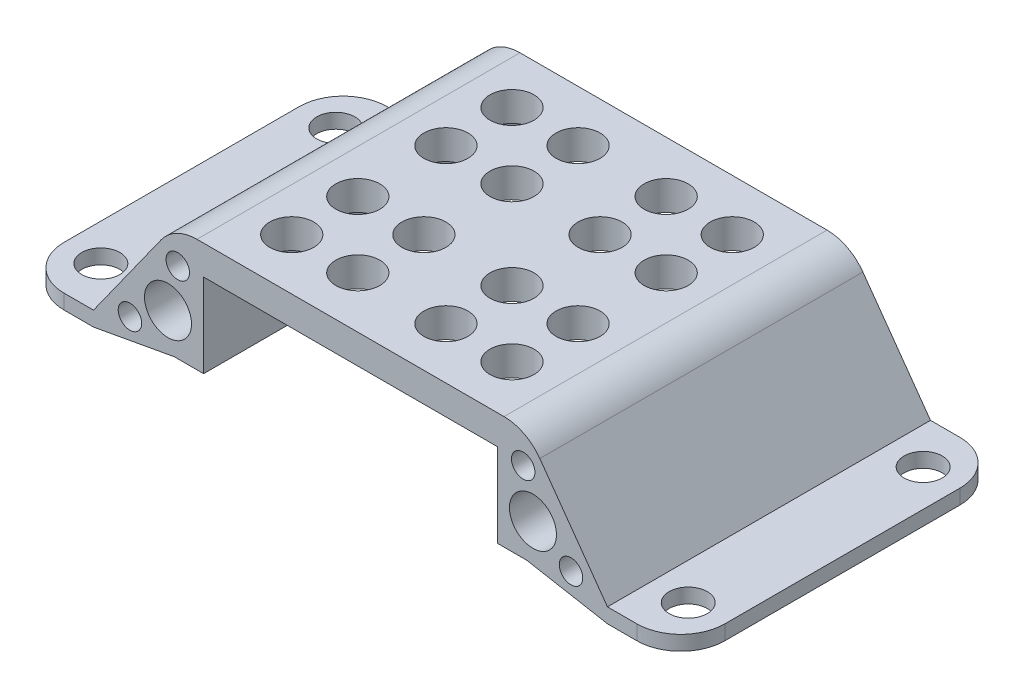
SolidWorks part; units mm, degrees
ref_plane "前视基准面" through (0, 0, 0) normal (0, 0, 1) x (1, 0, 0)
ref_plane "上视基准面" through (0, 0, 0) normal (0, 1, 0) x (1, 0, 0)
ref_plane "右视基准面" through (0, 0, 0) normal (1, 0, 0) x (0, 0, -1)
sketch "草图1" plane through (0, 0, 0) normal (0, 0, 1) x (1, 0, 0)
  line L0 (0, 0) -> (0, 12.8298) construction
  line L1 (12, 5.1298) -> (17.5, 4.1298)
  line L2 (0, 12.8298) -> (12, 12.8298)
  line L3 (0, 12.8298) -> (0, 10.8298)
  line L4 (0, 10.8298) -> (12, 10.8298)
  line L5 (12, 12.8298) -> (12, 10.8298)
  line L10 (17.5, 4.1298) -> (22.5, 4.1298)
  line L11 (17.5, 4.1298) -> (17.5, 5.1298)
  line L12 (17.5, 5.1298) -> (22.5, 5.1298)
  line L13 (22.5, 4.1298) -> (22.5, 5.1298)
  line L14 (10, 10.8298) -> (12, 10.8298)
  line L15 (10, 10.8298) -> (10, 5.1298)
  line L16 (10, 5.1298) -> (12, 5.1298)
  line L17 (12, 10.8298) -> (12, 5.1298)
  line L18 (12, 12.8298) -> (17.5, 5.1298)
  dimension "D1" = 2
  dimension "D2" = 17.5
  dimension "D3" = 1
  dimension "D4" = 6.7
  dimension "D5" = 5
  dimension "D7" = 2
  dimension "D8" = 5.7
  dimension "D9" = 10
extrude "凸台-拉伸1" add sketch "草图1" along normal blind 22
mirror "镜向1" about plane through (0, 0, 22) normal (1, 0, 0) of "凸台-拉伸1"
sketch "草图5" plane through (0, 0, 0) normal (0, 1, 0) x (1, 0, 0)
  line L0 (0, 0) -> (0, -22) construction
  line L1 (-12, -22) -> (12, -22) construction
  line L2 (-22.5, -11) -> (22.5, -11) construction
  line L3 (-22.5, -22) -> (-22.5, 0) construction
  line L4 (22.5, -22) -> (22.5, 0) construction
  circle A0 centre (-20, -3) radius 1.3
  circle A1 centre (-20, -19) radius 1.3
  circle A2 centre (20, -19) radius 1.3
  circle A3 centre (20, -3) radius 1.3
  dimension "D1" = 20
  dimension "D2" = 8
extrude "切除-拉伸2" cut sketch "草图5" along normal blind 19 contours A0 | A1 | A3 | A2
fillet "圆角1" radius 3 4 edges at (-22.5, 4.6298, 0) (-22.5, 4.6298, 22) (22.5, 4.6298, 0) (22.5, 4.6298, 22)
sketch "草图6" plane through (0, 0, 0) normal (0, 1, 0) x (1, 0, 0)
  line L0 (-22.5, -11) -> (22.5, -11) construction
  line L1 (-22.5, -19) -> (-22.5, -3) construction
  line L2 (22.5, -19) -> (22.5, -3) construction
  line L3 (0, 0) -> (0, -22) construction
  line L4 (-12, -22) -> (12, -22) construction
  circle A0 centre (-3, -8) radius 1.5
  circle A1 centre (-7.5, -8) radius 1.5
  circle A2 centre (-7.5, -3.5) radius 1.5
  circle A3 centre (-3, -3.5) radius 1.5
  circle A4 centre (-3, -14) radius 1.5
  circle A5 centre (-7.5, -14) radius 1.5
  circle A6 centre (-3, -18.5) radius 1.5
  circle A7 centre (-7.5, -18.5) radius 1.5
  circle A8 centre (3, -18.5) radius 1.5
  circle A9 centre (7.5, -18.5) radius 1.5
  circle A10 centre (3, -14) radius 1.5
  circle A11 centre (7.5, -14) radius 1.5
  circle A12 centre (3, -8) radius 1.5
  circle A13 centre (7.5, -8) radius 1.5
  circle A14 centre (3, -3.5) radius 1.5
  circle A15 centre (7.5, -3.5) radius 1.5
  dimension "D1" = 3
  dimension "D2" = 3
  dimension "D3" = 4.5
  dimension "D4" = 4.5
  dimension "D5" = 4.5
  dimension "D6" = 3
  dimension "D7" = 4.5
  dimension "D8" = 3
extrude "切除-拉伸3" cut sketch "草图6" along normal blind 30
sketch "草图7" plane through (0, 0, 0) normal (0, 0, 1) x (1, 0, 0)
  line L0 (0, 0) -> (0, 12.8298) construction
  line L1 (-12, 12.8298) -> (12, 12.8298) construction
  circle A0 centre (12.4261, 7.6444) radius 1.6
  circle A1 centre (15.0187, 5.9857) radius 0.8
  circle A2 centre (11.7626, 10.5933) radius 0.8
  circle A3 centre (-11.7626, 10.5933) radius 0.8
  circle A4 centre (-12.4261, 7.6444) radius 1.6
  circle A5 centre (-15.0187, 5.9857) radius 0.8
extrude "切除-拉伸4" cut sketch "草图7" along normal blind 27
fillet "圆角2" radius 3 2 edges at (-12, 12.8298, 11) (12, 12.8298, 11)
